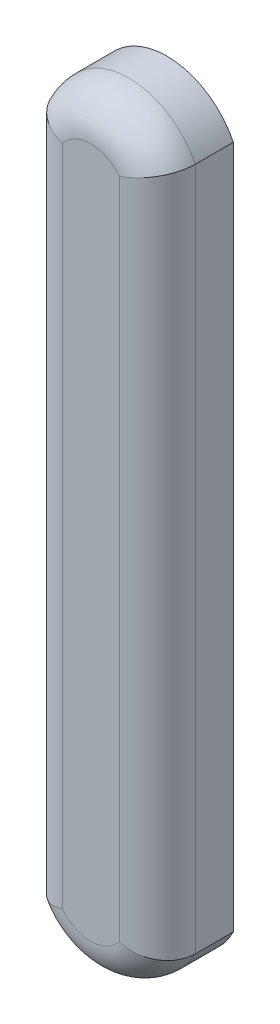
SolidWorks part; units mm, degrees
material "Plastique personnalisé"
ref_plane "Plan de face" through (0, 0, 0) normal (0, 0, 1) x (1, 0, 0)
ref_plane "Plan de dessus" through (0, 0, 0) normal (0, 1, 0) x (1, 0, 0)
ref_plane "Plan de droite" through (0, 0, 0) normal (1, 0, 0) x (0, 0, -1)
sketch "Esquisse1" plane through (0, 0, 0) normal (0, 0, 1) x (1, 0, 0)
  line L0 (0, 0.9) -> (0.35, 0.9) construction
  line L2 (0, 0) -> (0, 1.8)
  line L4 (0.35, 0) -> (0.35, 1.8)
  arc A0 (0, 1.8) -> (0.35, 1.8) centre (0.175, 1.714) cw
  arc A1 (0, 0) -> (0.35, 0) centre (0.175, 0.086) ccw
  dimension "D1" = 1.8
  dimension "D2" = 0.35
extrude "Boss.-Extru.1" add sketch "Esquisse1" along normal blind 0.2
fillet "Congé1" radius 0.1 4 edges at (0.175, -0.109, 0.2) (0, 0.9, 0.2) (0.35, 0.9, 0.2) (0.175, 1.909, 0.2)
